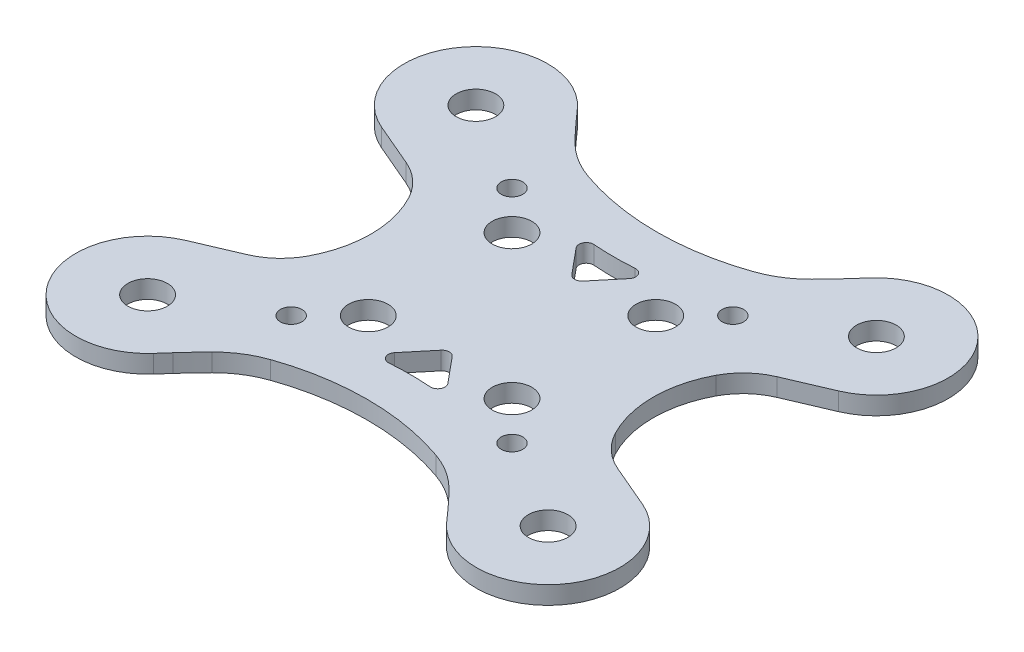
SolidWorks part; units mm, degrees
material "Thornel Mat VMA"
ref_plane "Front Plane" through (0, 0, 0) normal (0, 0, 1) x (1, 0, 0)
ref_plane "Top Plane" through (0, 0, 0) normal (0, 1, 0) x (1, 0, 0)
ref_plane "Right Plane" through (0, 0, 0) normal (1, 0, 0) x (0, 0, -1)
sketch "Sketch1" plane through (0, 0, 0) normal (0, 1, 0) x (1, 0, 0)
  line L0 (19.1123, 28.0515) -> (20.403, 29.4979)
  line L1 (31.7968, 13.6457) -> (25.7944, 11.0784)
  line L2 (25.7944, -11.0784) -> (31.7968, -13.6457)
  line L3 (20.403, -29.4979) -> (19.1123, -28.0515)
  line L4 (-19.1123, -28.0515) -> (-20.403, -29.4979)
  line L5 (-31.7968, -13.6457) -> (-25.7944, -11.0784)
  line L6 (-25.7944, 11.0784) -> (-31.7968, 13.6457)
  line L7 (-20.403, 29.4979) -> (-19.1123, 28.0515)
  line L8 (-0.7696, 9.0904) -> (-3.7105, 12.6352)
  line L9 (3.7105, 12.6352) -> (0.7696, 9.0904)
  line L10 (0.7696, -9.0904) -> (3.7105, -12.6352)
  line L11 (-3.7105, -12.6352) -> (-0.7696, -9.0904)
  circle A0 centre (27.8644, -22.84) radius 2.75
  circle A1 centre (-15.365, -15.365) radius 1.5
  circle A2 centre (15.365, 15.365) radius 1.5
  circle A3 centre (-15.365, 15.365) radius 1.5
  circle A4 centre (27.8644, 22.84) radius 2.75
  circle A5 centre (15.365, -15.365) radius 1.5
  circle A6 centre (10, 10) radius 2.75
  circle A7 centre (-10, 10) radius 2.75
  circle A8 centre (-10, -10) radius 2.75
  circle A9 centre (-27.8644, -22.84) radius 2.75
  circle A10 centre (-27.8644, 22.84) radius 2.75
  circle A11 centre (10, -10) radius 2.75
  arc A12 (16.4739, 25.2397) -> (19.1123, 28.0515) centre (-38.3402, 79.3175) ccw
  arc A13 (25.7944, 11.0784) -> (21.3765, 7.0088) centre (29.3336, 2.8035) ccw
  arc A14 (21.3765, 7.0088) -> (21.3765, -7.0088) centre (34.6384, 0) ccw
  arc A15 (21.3765, -7.0088) -> (25.7944, -11.0784) centre (29.3336, -2.8035) ccw
  arc A16 (20.403, -29.4979) -> (31.7968, -13.6457) centre (27.8644, -22.84) ccw
  arc A17 (19.1123, -28.0515) -> (16.4739, -25.2397) centre (-38.3402, -79.3175) ccw
  arc A18 (16.4739, -25.2397) -> (11.4857, -22.0897) centre (7.2196, -34.3697) ccw
  arc A19 (11.4857, -22.0897) -> (-11.4857, -22.0897) centre (0, -55.1514) ccw
  arc A20 (-11.4857, -22.0897) -> (-16.4739, -25.2397) centre (-7.2196, -34.3697) ccw
  arc A21 (-16.4739, -25.2397) -> (-19.1123, -28.0515) centre (38.3402, -79.3175) ccw
  arc A22 (-31.7968, -13.6457) -> (-20.403, -29.4979) centre (-27.8644, -22.84) ccw
  arc A23 (-25.7944, -11.0784) -> (-21.3765, -7.0088) centre (-29.3336, -2.8035) ccw
  arc A24 (-21.3765, -7.0088) -> (-21.3765, 7.0088) centre (-34.6384, 0) ccw
  arc A25 (-21.3765, 7.0088) -> (-25.7944, 11.0784) centre (-29.3336, 2.8035) ccw
  arc A26 (-20.403, 29.4979) -> (-31.7968, 13.6457) centre (-27.8644, 22.84) ccw
  arc A27 (-19.1123, 28.0515) -> (-16.4739, 25.2397) centre (38.3402, 79.3175) ccw
  arc A28 (-16.4739, 25.2397) -> (-11.4857, 22.0897) centre (-7.2196, 34.3697) ccw
  arc A29 (-11.4857, 22.0897) -> (11.4857, 22.0897) centre (0, 55.1514) ccw
  arc A30 (11.4857, 22.0897) -> (16.4739, 25.2397) centre (7.2196, 34.3697) ccw
  arc A31 (-0.7696, 9.0904) -> (0.7696, 9.0904) centre (0, 9.7289) ccw
  arc A32 (3.7105, 12.6352) -> (2.8655, 14.2709) centre (2.9409, 13.2737) ccw
  arc A33 (-2.8655, 14.2709) -> (2.8655, 14.2709) centre (0, 52.1627) ccw
  arc A34 (-2.8655, 14.2709) -> (-3.7105, 12.6352) centre (-2.9409, 13.2737) ccw
  arc A35 (2.8655, -14.2709) -> (3.7105, -12.6352) centre (2.9409, -13.2737) ccw
  arc A36 (0.7696, -9.0904) -> (-0.7696, -9.0904) centre (0, -9.7289) ccw
  arc A37 (-3.7105, -12.6352) -> (-2.8655, -14.2709) centre (-2.9409, -13.2737) ccw
  arc A38 (2.8655, -14.2709) -> (-2.8655, -14.2709) centre (0, -52.1627) ccw
  arc A39 (31.7968, 13.6457) -> (20.403, 29.4979) centre (27.8644, 22.84) ccw
sketch "Sketch2" plane through (0, 0, 0) normal (0, 1, 0) x (1, 0, 0)
  line L2 (3.7105, -12.6352) -> (0.7696, -9.0904)
  line L3 (-0.7696, -9.0904) -> (-3.7105, -12.6352)
  line L4 (3.7105, -12.6352) -> (0.7696, -9.0904)
  line L5 (-0.7696, -9.0904) -> (-3.7105, -12.6352)
  line L6 (-3.7105, 12.6352) -> (-0.7696, 9.0904)
  line L7 (0.7696, 9.0904) -> (3.7105, 12.6352)
  line L8 (-20.403, -29.4979) -> (-19.1123, -28.0515)
  line L9 (-25.7944, -11.0784) -> (-31.7968, -13.6457)
  line L10 (-31.7968, 13.6457) -> (-25.7944, 11.0784)
  line L11 (-19.1123, 28.0515) -> (-20.403, 29.4979)
  line L12 (20.403, 29.4979) -> (19.1123, 28.0515)
  line L13 (25.7944, 11.0784) -> (31.7968, 13.6457)
  line L14 (31.7968, -13.6457) -> (25.7944, -11.0784)
  line L15 (19.1123, -28.0515) -> (20.403, -29.4979)
  line L16 (-20.403, -29.4979) -> (-19.1123, -28.0515)
  line L17 (-25.7944, -11.0784) -> (-31.7968, -13.6457)
  line L18 (-31.7968, 13.6457) -> (-25.7944, 11.0784)
  line L19 (-19.1123, 28.0515) -> (-20.403, 29.4979)
  line L20 (20.403, 29.4979) -> (19.1123, 28.0515)
  line L21 (25.7944, 11.0784) -> (31.7968, 13.6457)
  line L22 (31.7968, -13.6457) -> (25.7944, -11.0784)
  line L23 (19.1123, -28.0515) -> (20.403, -29.4979)
  line L24 (-3.7105, 12.6352) -> (-0.7696, 9.0904)
  line L25 (0.7696, 9.0904) -> (3.7105, 12.6352)
  circle A1 centre (15.365, -15.365) radius 1.5
  circle A2 centre (15.365, -15.365) radius 1.5
  circle A3 centre (27.8644, 22.84) radius 2.75
  circle A4 centre (27.8644, 22.84) radius 2.75
  circle A5 centre (-15.365, 15.365) radius 1.5
  circle A6 centre (-15.365, 15.365) radius 1.5
  circle A7 centre (15.365, 15.365) radius 1.5
  circle A8 centre (15.365, 15.365) radius 1.5
  circle A9 centre (-15.365, -15.365) radius 1.5
  circle A10 centre (-15.365, -15.365) radius 1.5
  circle A11 centre (27.8644, -22.84) radius 2.75
  circle A12 centre (27.8644, -22.84) radius 2.75
  circle A13 centre (10, -10) radius 2.75
  circle A14 centre (10, -10) radius 2.75
  circle A15 centre (-27.8644, 22.84) radius 2.75
  circle A16 centre (-27.8644, 22.84) radius 2.75
  circle A17 centre (-27.8644, -22.84) radius 2.75
  circle A18 centre (-27.8644, -22.84) radius 2.75
  circle A19 centre (-10, -10) radius 2.75
  circle A20 centre (-10, -10) radius 2.75
  circle A21 centre (-10, 10) radius 2.75
  circle A22 centre (-10, 10) radius 2.75
  circle A23 centre (10, 10) radius 2.75
  circle A24 centre (10, 10) radius 2.75
  arc A28 (2.8655, -14.2709) -> (3.7105, -12.6352) centre (2.9409, -13.2737) ccw
  arc A29 (0.7696, -9.0904) -> (-0.7696, -9.0904) centre (0, -9.7289) ccw
  arc A30 (-3.7105, -12.6352) -> (-2.8655, -14.2709) centre (-2.9409, -13.2737) ccw
  arc A31 (2.8655, -14.2709) -> (-2.8655, -14.2709) centre (0, -52.1627) ccw
  arc A32 (2.8655, -14.2709) -> (3.7105, -12.6352) centre (2.9409, -13.2737) ccw
  arc A33 (0.7696, -9.0904) -> (-0.7696, -9.0904) centre (0, -9.7289) ccw
  arc A34 (-3.7105, -12.6352) -> (-2.8655, -14.2709) centre (-2.9409, -13.2737) ccw
  arc A35 (2.8655, -14.2709) -> (-2.8655, -14.2709) centre (0, -52.1627) ccw
  arc A36 (-2.8655, 14.2709) -> (2.8655, 14.2709) centre (0, 52.1627) ccw
  arc A37 (-2.8655, 14.2709) -> (-3.7105, 12.6352) centre (-2.9409, 13.2737) ccw
  arc A38 (-0.7696, 9.0904) -> (0.7696, 9.0904) centre (0, 9.7289) ccw
  arc A39 (3.7105, 12.6352) -> (2.8655, 14.2709) centre (2.9409, 13.2737) ccw
  arc A40 (-2.8655, 14.2709) -> (2.8655, 14.2709) centre (0, 52.1627) ccw
  arc A41 (-2.8655, 14.2709) -> (-3.7105, 12.6352) centre (-2.9409, 13.2737) ccw
  arc A42 (-0.7696, 9.0904) -> (0.7696, 9.0904) centre (0, 9.7289) ccw
  arc A43 (3.7105, 12.6352) -> (2.8655, 14.2709) centre (2.9409, 13.2737) ccw
  arc A44 (-16.4739, -25.2397) -> (-19.1123, -28.0515) centre (38.3402, -79.3175) ccw
  arc A45 (-31.7968, -13.6457) -> (-20.403, -29.4979) centre (-27.8644, -22.84) ccw
  arc A46 (-25.7944, -11.0784) -> (-21.3765, -7.0088) centre (-29.3336, -2.8035) ccw
  arc A47 (-21.3765, -7.0088) -> (-21.3765, 7.0088) centre (-34.6384, 0) ccw
  arc A48 (-21.3765, 7.0088) -> (-25.7944, 11.0784) centre (-29.3336, 2.8035) ccw
  arc A49 (-20.403, 29.4979) -> (-31.7968, 13.6457) centre (-27.8644, 22.84) ccw
  arc A50 (-19.1123, 28.0515) -> (-16.4739, 25.2397) centre (38.3402, 79.3175) ccw
  arc A51 (-16.4739, 25.2397) -> (-11.4857, 22.0897) centre (-7.2196, 34.3697) ccw
  arc A52 (-11.4857, 22.0897) -> (11.4857, 22.0897) centre (0, 55.1514) ccw
  arc A53 (11.4857, 22.0897) -> (16.4739, 25.2397) centre (7.2196, 34.3697) ccw
  arc A54 (16.4739, 25.2397) -> (19.1123, 28.0515) centre (-38.3402, 79.3175) ccw
  arc A55 (31.7968, 13.6457) -> (20.403, 29.4979) centre (27.8644, 22.84) ccw
  arc A56 (25.7944, 11.0784) -> (21.3765, 7.0088) centre (29.3336, 2.8035) ccw
  arc A57 (21.3765, 7.0088) -> (21.3765, -7.0088) centre (34.6384, 0) ccw
  arc A58 (21.3765, -7.0088) -> (25.7944, -11.0784) centre (29.3336, -2.8035) ccw
  arc A59 (20.403, -29.4979) -> (31.7968, -13.6457) centre (27.8644, -22.84) ccw
  arc A60 (19.1123, -28.0515) -> (16.4739, -25.2397) centre (-38.3402, -79.3175) ccw
  arc A61 (16.4739, -25.2397) -> (11.4857, -22.0897) centre (7.2196, -34.3697) ccw
  arc A62 (11.4857, -22.0897) -> (-11.4857, -22.0897) centre (0, -55.1514) ccw
  arc A63 (-11.4857, -22.0897) -> (-16.4739, -25.2397) centre (-7.2196, -34.3697) ccw
  arc A64 (-16.4739, -25.2397) -> (-19.1123, -28.0515) centre (38.3402, -79.3175) ccw
  arc A65 (-31.7968, -13.6457) -> (-20.403, -29.4979) centre (-27.8644, -22.84) ccw
  arc A66 (-25.7944, -11.0784) -> (-21.3765, -7.0088) centre (-29.3336, -2.8035) ccw
  arc A67 (-21.3765, -7.0088) -> (-21.3765, 7.0088) centre (-34.6384, 0) ccw
  arc A68 (-21.3765, 7.0088) -> (-25.7944, 11.0784) centre (-29.3336, 2.8035) ccw
  arc A69 (-20.403, 29.4979) -> (-31.7968, 13.6457) centre (-27.8644, 22.84) ccw
  arc A70 (-19.1123, 28.0515) -> (-16.4739, 25.2397) centre (38.3402, 79.3175) ccw
  arc A71 (-16.4739, 25.2397) -> (-11.4857, 22.0897) centre (-7.2196, 34.3697) ccw
  arc A72 (-11.4857, 22.0897) -> (11.4857, 22.0897) centre (0, 55.1514) ccw
  arc A73 (11.4857, 22.0897) -> (16.4739, 25.2397) centre (7.2196, 34.3697) ccw
  arc A74 (16.4739, 25.2397) -> (19.1123, 28.0515) centre (-38.3402, 79.3175) ccw
  arc A75 (31.7968, 13.6457) -> (20.403, 29.4979) centre (27.8644, 22.84) ccw
  arc A76 (25.7944, 11.0784) -> (21.3765, 7.0088) centre (29.3336, 2.8035) ccw
  arc A77 (21.3765, 7.0088) -> (21.3765, -7.0088) centre (34.6384, 0) ccw
  arc A78 (21.3765, -7.0088) -> (25.7944, -11.0784) centre (29.3336, -2.8035) ccw
  arc A79 (20.403, -29.4979) -> (31.7968, -13.6457) centre (27.8644, -22.84) ccw
  arc A80 (19.1123, -28.0515) -> (16.4739, -25.2397) centre (-38.3402, -79.3175) ccw
  arc A81 (16.4739, -25.2397) -> (11.4857, -22.0897) centre (7.2196, -34.3697) ccw
  arc A82 (11.4857, -22.0897) -> (-11.4857, -22.0897) centre (0, -55.1514) ccw
  arc A83 (-11.4857, -22.0897) -> (-16.4739, -25.2397) centre (-7.2196, -34.3697) ccw
  point P0 (0, 0)
  dimension "D1" = 0
  dimension "D2" = 0
  dimension "D3" = 0
  dimension "D4" = 0
  dimension "D5" = 0
  dimension "D6" = 0
  dimension "D7" = 0
  dimension "D8" = 0
  dimension "D9" = 0
  dimension "D10" = 0
  dimension "D11" = 0
  dimension "D12" = 0
  dimension "D13" = 0
  dimension "D14" = 0
  dimension "D15" = 0
extrude "Boss-Extrude1" add sketch "Sketch2" along normal blind 2.5
